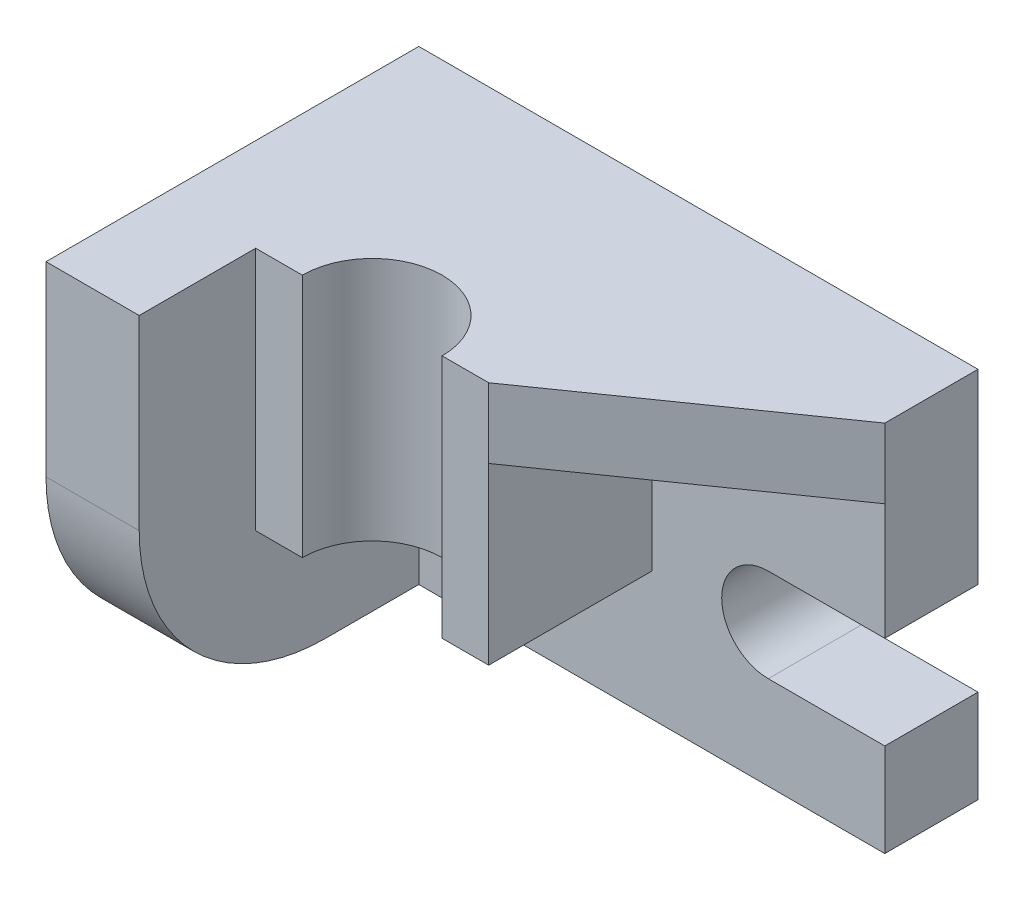
SolidWorks part; units mm, degrees
ref_plane "Front Plane" through (0, 0, 0) normal (0, 0, 1) x (1, 0, 0)
ref_plane "Top Plane" through (0, 0, 0) normal (0, 1, 0) x (1, 0, 0)
ref_plane "Right Plane" through (0, 0, 0) normal (1, 0, 0) x (0, 0, -1)
sketch "Sketch1" plane through (0, 0, 0) normal (0, 0, 1) x (1, 0, 0)
  line L0 (0, 0) -> (96, 0)
  line L1 (96, 0) -> (96, 64)
  line L2 (96, 64) -> (0, 64)
  line L3 (0, 64) -> (0, 0)
  dimension "D1" = 64
  dimension "D2" = 96
extrude "Boss-Extrude1" add sketch "Sketch1" along normal blind 16
ref_plane "Plane1" through (16, 0, 0) normal (-1, 0, 0) x (0, 0, 1)
sketch "Sketch3" plane through (16, 0, 0) normal (-1, 0, 0) x (0, 0, 1)
  line L1 (16, 0) -> (16, 64)
  line L2 (16, 64) -> (64, 64)
  line L3 (64, 64) -> (64, 32)
  line L4 (32, 0) -> (16, 0)
  arc A0 (64, 32) -> (32, 0) centre (32, 32) cw
  dimension "D1" = 32
  dimension "D2" = 64
extrude "Boss-Extrude2" add sketch "Sketch3" along normal blind 16
sketch "Sketch4" plane through (0, 64, 0) normal (0, 1, 0) x (1, 0, 0)
  line L0 (16, -16) -> (56, -16)
  line L1 (96, -16) -> (16, -16) construction
  line L2 (56, -16) -> (56, -44)
  line L3 (56, -44) -> (48, -44)
  line L4 (16, -16) -> (16, -44)
  line L5 (16, -64) -> (16, -16) construction
  line L6 (16, -44) -> (24, -44)
  line L7 (0, -64) -> (0, 0) construction
  line L8 (96, 0) -> (0, 0) construction
  arc A0 (48, -44) -> (24, -44) centre (36, -44) ccw
  dimension "D1" = 12
  dimension "D2" = 36
  dimension "D3" = 44
extrude "Boss-Extrude3" add sketch "Sketch4" against normal blind 42
sketch "Sketch5" plane through (0, 64, 0) normal (0, 1, 0) x (1, 0, 0)
  line L0 (96, -16) -> (56, -16)
  line L1 (56, -16) -> (56, -44)
  line L2 (56, -44) -> (96, -16)
extrude "Boss-Extrude4" add sketch "Sketch5" against normal blind 12
sketch "Sketch6" plane through (0, 0, 16) normal (0, 0, 1) x (1, 0, 0)
  line L0 (56, 22) -> (56, 52) construction
  line L1 (96, 0) -> (96, 52) construction
  line L2 (96, 16) -> (96, 32)
  line L3 (96, 32) -> (76, 32)
  line L4 (96, 16) -> (76, 16)
  line L5 (96, 52) -> (56, 52) construction
  arc A0 (76, 32) -> (76, 16) centre (76, 24) ccw
  dimension "D1" = 8
  dimension "D2" = 20
  dimension "D3" = 28
extrude "Cut-Extrude2" cut sketch "Sketch6" against normal blind 16
